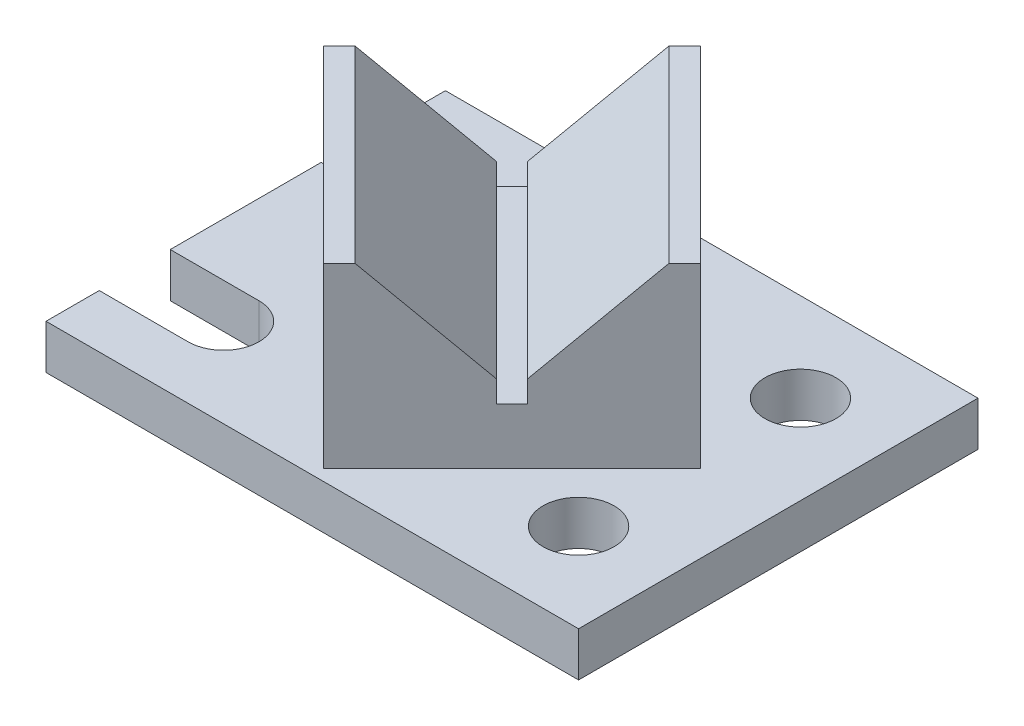
SolidWorks part; units mm, degrees
ref_plane "Front Plane" through (0, 0, 0) normal (0, 0, 1) x (1, 0, 0)
ref_plane "Top Plane" through (0, 0, 0) normal (0, 1, 0) x (1, 0, 0)
ref_plane "Right Plane" through (0, 0, 0) normal (1, 0, 0) x (0, 0, -1)
sketch "Croquis2" plane through (0, 0, 0) normal (0, 1, 0) x (1, 0, 0)
  line L1 (-76.2, -57.15) -> (76.2, -57.15)
  line L2 (-76.2, -57.15) -> (-76.2, 57.15)
  line L3 (-76.2, 57.15) -> (76.2, 57.15)
  line L4 (76.2, -57.15) -> (76.2, 57.15)
  line L5 (-76.2, -57.15) -> (76.2, 57.15) construction
  line L6 (-76.2, 57.15) -> (76.2, -57.15) construction
  point P0 (0, 0)
  dimension "D1" = 152.4
  dimension "D2" = 114.3
extrude "Saliente-Extruir1" add sketch "Croquis2" along normal blind 12.7
sketch "Croquis3" plane through (0, 12.7, 0) normal (0, 1, 0) x (1, 0, 0)
  line L0 (-76.2, -57.15) -> (76.2, -57.15) construction
  line L1 (76.2, -57.15) -> (76.2, 57.15) construction
  line L2 (-76.2, 57.15) -> (-76.2, -57.15) construction
  line L3 (-76.2, -21.59) -> (-50.8, -21.59)
  line L4 (-76.2, -21.59) -> (-76.2, -41.91) construction
  line L5 (-76.2, -41.91) -> (-50.8, -41.91)
  line L7 (-76.2, -31.75) -> (-45.3029, -31.75) construction
  line L8 (-50.8, -21.59) -> (-50.8, -41.91) construction
  line L9 (-76.2, -21.59) -> (-76.2, -41.91)
  circle A0 centre (50.8, -31.75) radius 10.16
  arc A1 (-50.8, -21.59) -> (-50.8, -41.91) centre (-50.8, -31.75) cw
  dimension "D1" = 20.32
  dimension "D2" = 25.4
  dimension "D3" = 25.4
  dimension "D4" = 25.4
  dimension "D5" = 20.32
  dimension "D6" = 25.4
extrude "Cortar-Extruir2" cut sketch "Croquis3" against normal through all
mirror "Simetría2" about plane through (0, 0, 0) normal (0, 0, 1) of "Cortar-Extruir2"
sketch "Croquis5" plane through (0, 12.7, 0) normal (0, 1, 0) x (1, 0, 0)
  line L1 (0, -53.8815) -> (53.8815, 0)
  line L2 (0, -53.8815) -> (-53.8815, 0)
  line L3 (-53.8815, 0) -> (0, 53.8815)
  line L4 (53.8815, 0) -> (0, 53.8815)
  line L5 (0, -53.8815) -> (0, 53.8815) construction
  line L6 (-53.8815, 0) -> (53.8815, 0) construction
  point P0 (0, 0)
  dimension "D1" = 76.2
extrude "Saliente-Extruir2" add sketch "Croquis5" along normal blind 50.8
sketch "Croquis7" plane through (26.9408, 0, 26.9408) normal (0.7071, 0, 0.7071) x (0.7071, 0, -0.7071)
  line L0 (0, 63.5) -> (0, 12.7) construction
  line L1 (-38.1, 63.5) -> (38.1, 63.5) construction
  line L2 (-38.1, 12.7) -> (38.1, 12.7) construction
  line L3 (-31.75, 63.5) -> (31.75, 63.5)
  line L4 (31.75, 63.5) -> (3.175, 34.925)
  line L5 (3.175, 34.925) -> (3.175, 28.702)
  line L6 (3.175, 28.702) -> (-3.175, 28.702)
  line L7 (-3.175, 34.925) -> (-3.175, 28.702)
  line L8 (-31.75, 63.5) -> (-3.175, 34.925)
  point P9 (0, 63.5)
  point P13 (0, 28.702)
  dimension "D1" = 6.35
  dimension "D2" = 16.002
  dimension "D3" = 6.35
  dimension "D4" = 90
extrude "Cortar-Extruir3" cut sketch "Croquis7" against normal through all
